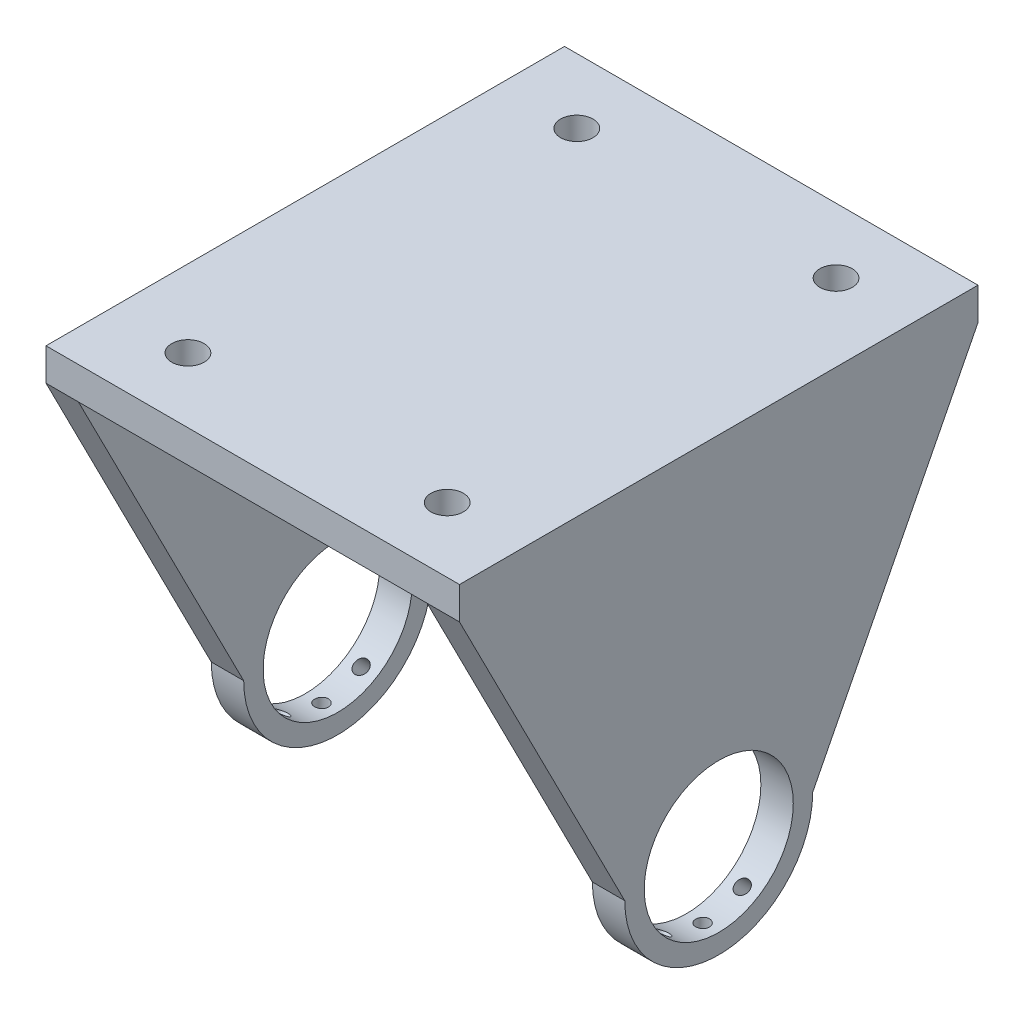
SolidWorks part; units mm, degrees
material "7075-O (SS)"
ref_plane "Front Plane" through (0, 0, 0) normal (0, 0, 1) x (1, 0, 0)
ref_plane "Top Plane" through (0, 0, 0) normal (0, 1, 0) x (1, 0, 0)
ref_plane "Right Plane" through (0, 0, 0) normal (1, 0, 0) x (0, 0, -1)
sketch "Sketch2" plane through (0, 0, 0) normal (0, 1, 0) x (1, 0, 0)
  line L1 (-40.513, 50.8) -> (40.513, 50.8)
  line L2 (-40.513, 50.8) -> (-40.513, -50.8)
  line L3 (-40.513, -50.8) -> (40.513, -50.8)
  line L4 (40.513, 50.8) -> (40.513, -50.8)
  line L5 (-40.513, 50.8) -> (40.513, -50.8) construction
  line L6 (-40.513, -50.8) -> (40.513, 50.8) construction
  point P0 (0, 0)
  dimension "D1" = 81.026
  dimension "D2" = 101.6
extrude "Boss-Extrude1" add sketch "Sketch2" along normal blind 6.35
sketch "Sketch3" plane through (40.513, 0, 0) normal (1, 0, 0) x (0, 0, -1)
  line L0 (-50.8, 6.35) -> (-50.8, 0)
  line L1 (-50.8, 0) -> (-18.415, -63.5)
  line L2 (18.415, -63.5) -> (50.8, 0)
  line L3 (50.8, 0) -> (50.8, 6.35)
  line L4 (50.8, 6.35) -> (-50.8, 6.35)
  line L5 (-50.8, 0) -> (50.8, 0) construction
  arc A0 (-18.415, -63.5) -> (18.415, -63.5) centre (0, -63.5) ccw
  circle A1 centre (0, -63.5) radius 14.605
  point P7 (0, 0)
  dimension "D2" = 18.415
  dimension "D3" = 29.21
  dimension "D1" = 63.5
extrude "Boss-Extrude2" add sketch "Sketch3" against normal blind 6.35
ref_plane "Plane1" through (0, -81.915, 0) normal (0, -1, 0) x (-1, 0, 0)
sketch "Sketch5" plane through (0, -81.915, 0) normal (0, -1, 0) x (-1, 0, 0)
  line L0 (-40.513, 0) -> (-37.338, 0) construction
  line L1 (-40.513, 18.415) -> (-40.513, -18.415) construction
  line L2 (-37.338, 0) -> (-34.163, 0) construction
  line L3 (-34.163, -50.8) -> (-34.163, 50.8) construction
  circle A0 centre (-37.338, 0) radius 1.3526
  dimension "D1" = 2.7051
extrude "Cut-Extrude1" cut sketch "Sketch5" against normal blind 16.256
ref_plane "Plane2" through (0, -18.7286, -18.7286) normal (0, 0.7071, 0.7071) x (1, 0, 0)
ref_plane "Plane3" through (0, -45.6694, -45.6694) normal (0, 0.7071, 0.7071) x (1, 0, 0)
sketch "Sketch6" plane through (0, -45.6694, -45.6694) normal (0, 0.7071, 0.7071) x (1, 0, 0)
  circle A0 centre (37.3393, -48.118) radius 1.3526
  point P2 (37.3393, -48.118)
  dimension "D1" = 2.7051
extrude "Cut-Extrude2" cut sketch "Sketch6" along normal blind 9.652
mirror "Mirror1" about plane through (0, 0, 0) normal (0, 0, 1) of "Cut-Extrude2"
mirror "Mirror2" about plane through (0, 0, 0) normal (1, 0, 0) of "Mirror1", "Cut-Extrude2", "Cut-Extrude1", "Boss-Extrude2"
sketch "Sketch7" plane through (0, 0, 0) normal (0, -1, 0) x (1, 0, 0)
  line L1 (-25.4, 38.1) -> (25.4, 38.1) construction
  line L2 (-25.4, 38.1) -> (-25.4, -38.1) construction
  line L3 (-25.4, -38.1) -> (25.4, -38.1) construction
  line L4 (25.4, 38.1) -> (25.4, -38.1) construction
  line L5 (-25.4, 38.1) -> (25.4, -38.1) construction
  line L6 (-25.4, -38.1) -> (25.4, 38.1) construction
  circle A0 centre (-25.4, 38.1) radius 3.175
  circle A1 centre (25.4, 38.1) radius 3.175
  circle A2 centre (25.4, -38.1) radius 3.175
  circle A3 centre (-25.4, -38.1) radius 3.175
  point P0 (0, 0)
  dimension "D3" = 6.35
  dimension "D1" = 76.2
  dimension "D2" = 50.8
extrude "Cut-Extrude3" cut sketch "Sketch7" against normal up to surface (6.35 mm away) up to face at (0, 6.35, 0)
